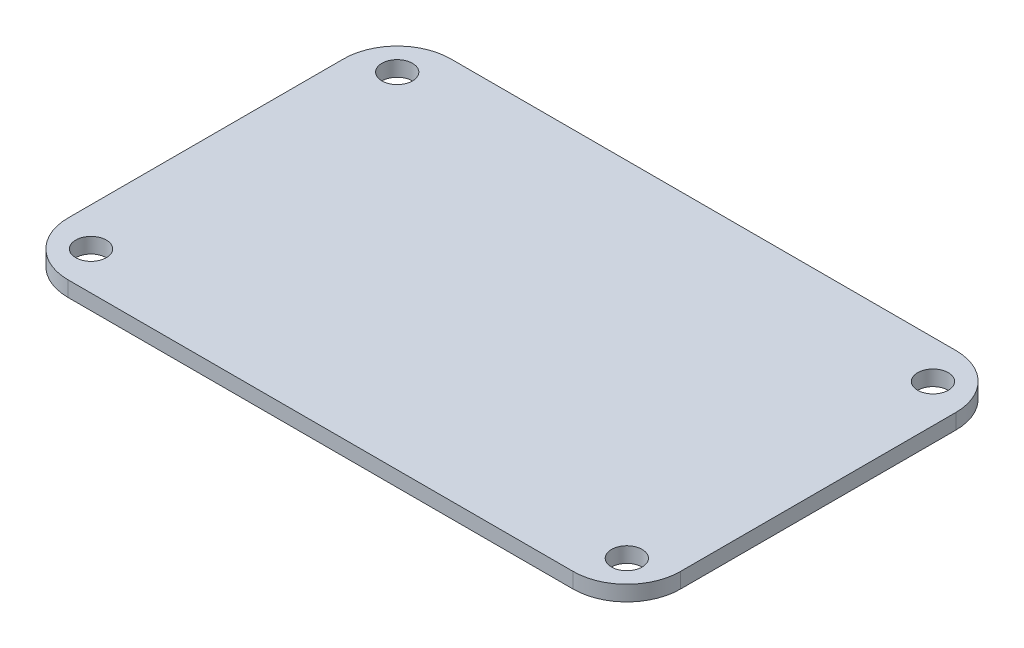
SolidWorks part; units mm, degrees
ref_plane "Front Plane" through (0, 0, 0) normal (0, 0, 1) x (1, 0, 0)
ref_plane "Top Plane" through (0, 0, 0) normal (0, 1, 0) x (1, 0, 0)
ref_plane "Right Plane" through (0, 0, 0) normal (1, 0, 0) x (0, 0, -1)
sketch "Sketch_lid" plane through (0, 0, 0) normal (0, 1, 0) x (1, 0, 0)
  line L1 (-40, 25) -> (40, 25)
  line L2 (-40, 25) -> (-40, -25)
  line L3 (-40, -25) -> (40, -25)
  line L4 (40, 25) -> (40, -25)
  line L5 (-40, 25) -> (40, -25) construction
  line L6 (-40, -25) -> (40, 25) construction
  point P0 (0, 0)
  dimension "D1" = 80
  dimension "D2" = 50
extrude "Boss-Extrude_lid" add sketch "Sketch_lid" along normal blind 2
fillet "Fillet_corners" radius 7 4 edges at (-40, 1, 25) (-40, 1, -25) (40, 1, -25) (40, 1, 25)
sketch "Sketch_screw_hole" plane through (0, 0, 0) normal (0, -1, 0) x (1, 0, 0)
  circle A0 centre (-35, -20) radius 2 construction
  circle A1 centre (35, -20) radius 2 construction
  circle A2 centre (35, 20) radius 2 construction
  circle A3 centre (-35, 20) radius 2 construction
  circle A4 centre (-35, -20) radius 2
  circle A5 centre (35, -20) radius 2
  circle A6 centre (35, 20) radius 2
  circle A7 centre (-35, 20) radius 2
extrude "Cut-Extrude_screw_hole" cut sketch "Sketch_screw_hole" against normal up to surface (2 mm away) up to face at (0, 2, 0)
equation "\"Length\"= 90"
equation "\"Width\"= 60"
equation "\"Height\"= 16"
equation "\"R1_main_radius\"= 12"
equation "\"R2\"= 5'Bottom radius"
equation "\"R3\"= 3'Top radius"
equation "\"Wall_Thickness\"= 2'Thickness of the wall"
equation "\"Screw_tower_outer_d\"= 6"
equation "\"Screw_tower_inner_d\"= 3"
equation "\"Tower_D1\"= 10"
equation "\"Tower_D2\"= 5"
equation "\"Tower_height\"= \"Height\" - 2 * \"Wall_Thickness\""
equation "\"Width2\"= \"Width\" - 2 * \"R2\""
equation "\"Length2\"= \"Length\" - 2 * \"R2\""
equation "\"D1@Sketch_lid\" = \"Length2\""
equation "\"D2@Sketch_lid\" = \"Width2\""
equation "\"D1@Boss-Extrude_lid\" = \"Wall_Thickness\""
equation "\"R4\"= 7"
equation "\"D1@Fillet_corners\" = \"R4\""
